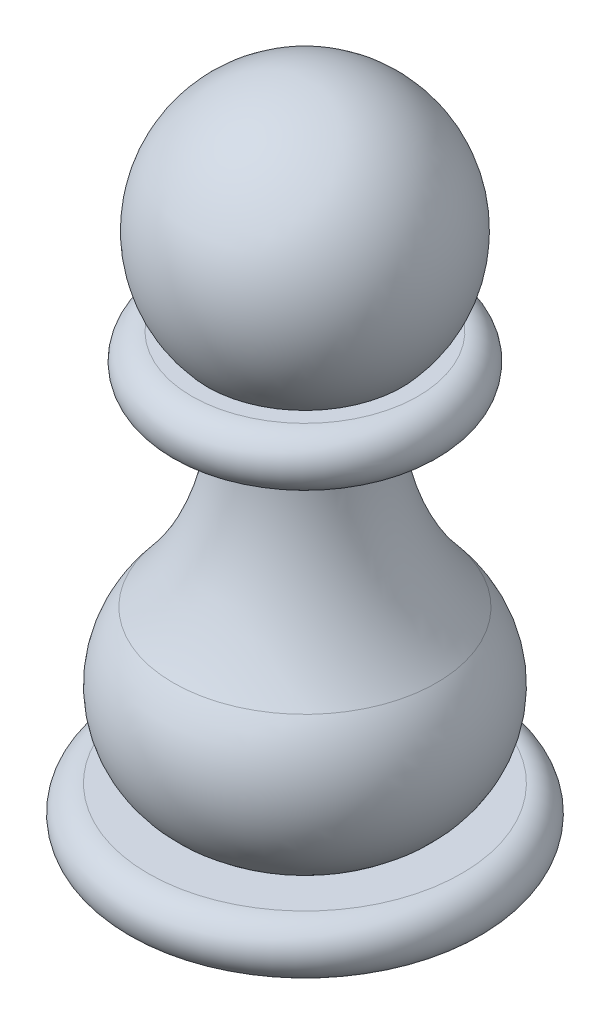
SolidWorks part; units mm, degrees
material "ABS"
ref_plane "Front Plane" through (0, 0, 0) normal (0, 0, 1) x (1, 0, 0)
ref_plane "Top Plane" through (0, 0, 0) normal (0, 1, 0) x (1, 0, 0)
ref_plane "Right Plane" through (0, 0, 0) normal (1, 0, 0) x (0, 0, -1)
sketch "Sketch2" plane through (0, 0, 0) normal (1, 0, 0) x (0, 0, -1)
  line L0 (0, 0) -> (0, -38)
  line L1 (0, -38) -> (9, -38)
  line L3 (5.5902, -12.5) -> (6.5, -12.5)
  line L4 (6.5, -15.5) -> (4, -15.5)
  line L6 (9, -35) -> (6.5, -35)
  line L7 (9, -22.8365) -> (9, -30.1491) construction
  arc A0 (9, -38) -> (9, -35) centre (9, -36.5) ccw
  arc A4 (5.5902, -12.5) -> (0, 0) centre (0, -7.5) ccw
  arc A5 (6.5, -12.5) -> (6.5, -15.5) centre (6.5, -14) cw
  arc A6 (4, -15.5) -> (7.5621, -26.2296) centre (18.9675, -16.487) ccw
  arc A8 (7.5621, -26.2296) -> (6.5, -35) centre (3, -30.1266) cw
  dimension "D1" = 1.5
  dimension "D4" = 7.5
  dimension "D7" = 6
  dimension "D10" = 15
  dimension "D3" = 38
  dimension "D5" = 9
  dimension "D6" = 12.5
  dimension "D8" = 6.5
  dimension "D9" = 4
  dimension "D11" = 6.5
  dimension "D2" = 9
revolve "Revolve1" add sketch "Sketch2" angle 360 about L0
equation "\"A\"=38"
equation "\"D3@Sketch2\"=\"A\""
